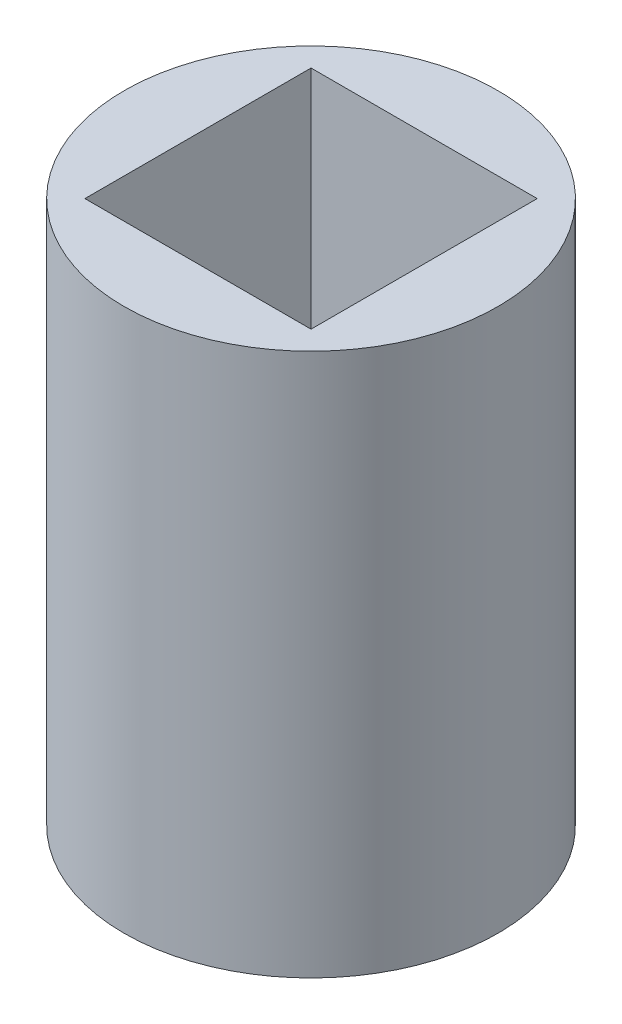
SolidWorks part; units mm, degrees
ref_plane "Front Plane" through (0, 0, 0) normal (0, 0, 1) x (1, 0, 0)
ref_plane "Top Plane" through (0, 0, 0) normal (0, 1, 0) x (1, 0, 0)
ref_plane "Right Plane" through (0, 0, 0) normal (1, 0, 0) x (0, 0, -1)
sketch "Sketch1" plane through (0, 0, 0) normal (0, 1, 0) x (1, 0, 0)
  line L1 (-4.7625, -4.7625) -> (4.7625, -4.7625)
  line L2 (-4.7625, -4.7625) -> (-4.7625, 4.7625)
  line L3 (-4.7625, 4.7625) -> (4.7625, 4.7625)
  line L4 (4.7625, -4.7625) -> (4.7625, 4.7625)
  line L5 (-4.7625, -4.7625) -> (4.7625, 4.7625) construction
  line L6 (-4.7625, 4.7625) -> (4.7625, -4.7625) construction
  circle A0 centre (0, 0) radius 7.874
  dimension "D1" = 15.748
  dimension "D2" = 9.525
  dimension "D3" = 9.525
extrude "Boss-Extrude1" add sketch "Sketch1" along normal blind 22.86
